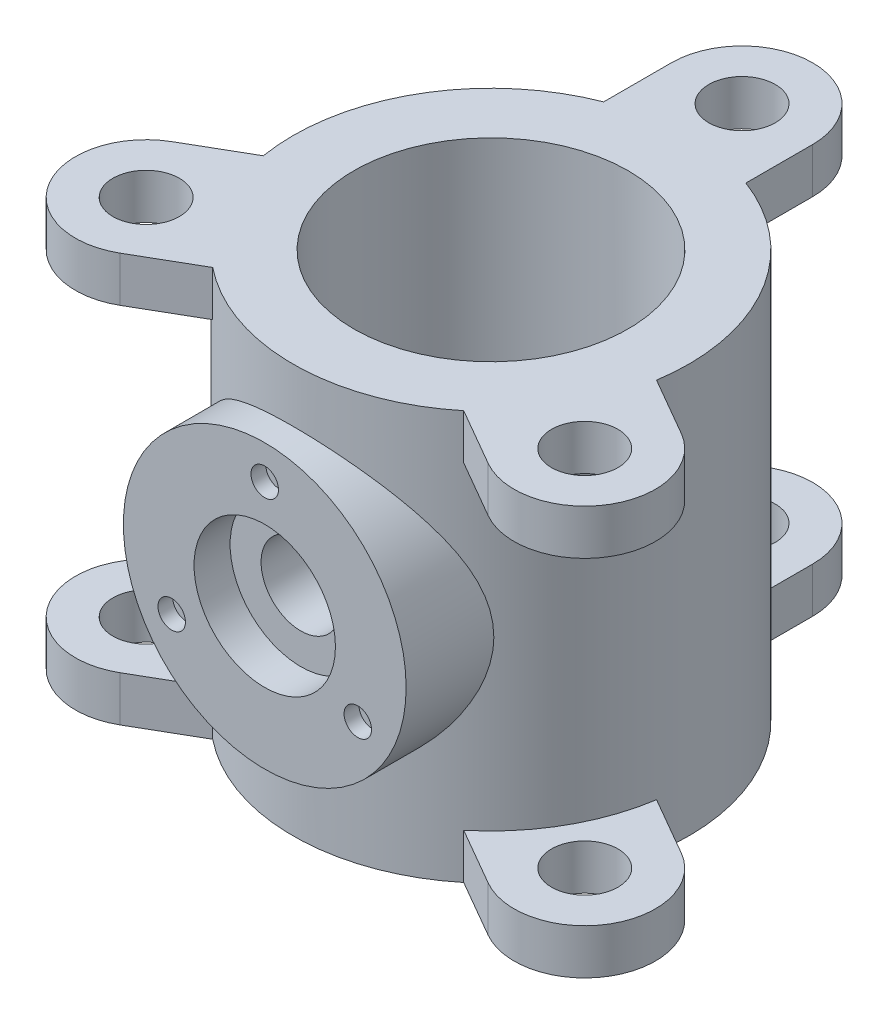
SolidWorks part; units mm, degrees
ref_plane "Front Plane" through (0, 0, 0) normal (0, 0, 1) x (1, 0, 0)
ref_plane "Top Plane" through (0, 0, 0) normal (0, 1, 0) x (1, 0, 0)
ref_plane "Right Plane" through (0, 0, 0) normal (1, 0, 0) x (0, 0, -1)
sketch "Sketch2" plane through (0, 0, 0) normal (0, 1, 0) x (1, 0, 0)
  line L0 (0, 140) -> (0, 154.8519) construction
  line L1 (-50.769, 178.3393) -> (-50.769, 130.4703)
  line L2 (49.231, 178.3393) -> (49.231, 131.0584)
  line L3 (179.8309, -45.2024) -> (138.3751, -21.2679)
  line L4 (129.8309, -131.8049) -> (88.8844, -108.1645)
  line L5 (-129.0618, -133.1369) -> (-87.6061, -109.2024)
  line L6 (-179.0618, -46.5344) -> (-138.1154, -22.8939)
  circle A0 centre (0, 0) radius 140
  circle A1 centre (0, 0) radius 97
  arc A2 (49.231, 178.3393) -> (-50.769, 178.3393) centre (-0.769, 178.3393) ccw
  circle A3 centre (-0.769, 178.3393) radius 23.5
  arc A4 (129.8309, -131.8049) -> (179.8309, -45.2024) centre (154.8309, -88.5037) ccw
  circle A5 centre (154.8309, -88.5037) radius 23.5
  arc A6 (-179.0618, -46.5344) -> (-129.0618, -133.1369) centre (-154.0618, -89.8356) ccw
  circle A7 centre (-154.0618, -89.8356) radius 23.5
  point P26 (0, 0)
  dimension "D1" = 140
  dimension "D2" = 194
  dimension "D3" = 50
  dimension "D4" = 47
  dimension "D5" = 3
extrude "Boss-Extrude5" add sketch "Sketch2" along normal blind 32
sketch "Sketch3" plane through (0, 32, 0) normal (0, 1, 0) x (1, 0, 0)
  circle A0 centre (0, 0) radius 140
  circle A1 centre (0, 0) radius 97
extrude "Boss-Extrude8" add sketch "Sketch3" along normal blind 112.5
mirror "Mirror1" about plane through (0, 144.5, 0) normal (0, 1, 0) of bodies 112
ref_plane "Plane1" through (0, 0, 160) normal (0, 0, 1) x (1, 0, 0)
sketch "Sketch4" plane through (0, 0, 160) normal (0, 0, 1) x (1, 0, 0)
  line L0 (0, 301.8008) -> (0, 0) construction
  circle A0 centre (0, 150.9004) radius 100
  circle A1 centre (0, 150.9004) radius 50
  circle A2 centre (0, 150.9004) radius 28.1
  dimension "D1" = 200
  dimension "D2" = 100
  dimension "D3" = 56.2
extrude "Boss-Extrude10" add sketch "Sketch4" against normal up to surface (62.0204 mm away) contours A0
sketch "Sketch5" plane through (0, 0, 160) normal (0, 0, 1) x (1, 0, 0)
  circle A0 centre (0, 150.9004) radius 50
  dimension "D1" = 100
extrude "Cut-Extrude1" cut sketch "Sketch5" against normal blind 25.5
sketch "Sketch7" plane through (0, 0, 134.5) normal (0, 0, 1) x (1, 0, 0)
  circle A0 centre (0, 150.9004) radius 28.1
  dimension "D1" = 56.2
extrude "Cut-Extrude2" cut sketch "Sketch7" against normal blind 328.5
sketch "Sketch9" plane through (0, 0, 160) normal (0, 0, 1) x (1, 0, 0)
  circle A0 centre (0, 226.8957) radius 9.7144
  circle A1 centre (0, 150.9004) radius 76.6237
  circle A2 centre (65.8138, 112.9028) radius 9.7144
  circle A3 centre (-65.8138, 112.9028) radius 9.7144
  point P11 (0, 150.9004)
  dimension "D1" = 19.4287
  dimension "D2" = 3
extrude "Cut-Extrude3" cut sketch "Sketch9" against normal blind 10.5 contours A0 | A3 | A2
